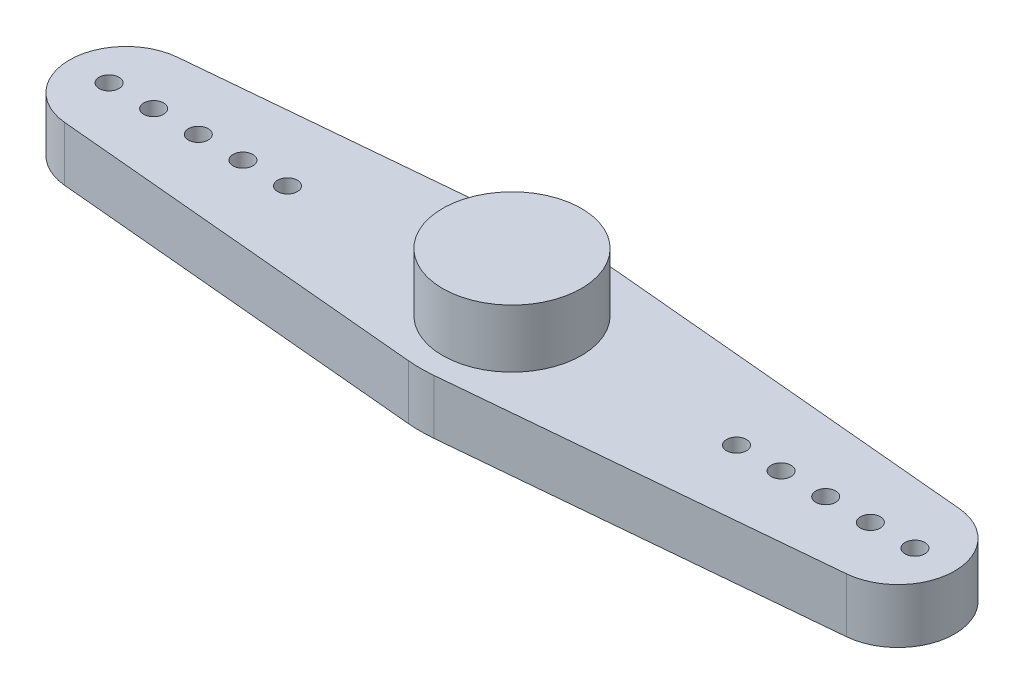
SolidWorks part; units mm, degrees
ref_plane "Front Plane" through (0, 0, 0) normal (0, 0, 1) x (1, 0, 0)
ref_plane "Top Plane" through (0, 0, 0) normal (0, 1, 0) x (1, 0, 0)
ref_plane "Right Plane" through (0, 0, 0) normal (1, 0, 0) x (0, 0, -1)
sketch "Sketch1" plane through (0, 0, 0) normal (0, 1, 0) x (1, 0, 0)
  line L0 (-27.25, 0) -> (27.25, 0) construction
  line L1 (27.613, 3.9835) -> (0, 6.5)
  line L2 (0, -6.5) -> (27.613, -3.9835)
  line L3 (28.45, 0) -> (25.3, 0) construction
  line L4 (0, -6.5) -> (0, 6.5) construction
  line L5 (-28.45, 0) -> (-25.3, 0) construction
  line L6 (0, -6.5) -> (-27.613, -3.9835)
  line L7 (-27.613, 3.9835) -> (0, 6.5)
  circle A0 centre (0, 0) radius 6.5 construction
  arc A1 (27.613, -3.9835) -> (27.613, 3.9835) centre (27.25, 0) ccw
  circle A2 centre (28.45, 0) radius 0.7
  circle A7 centre (25.3, 0) radius 0.7
  circle A8 centre (22.15, 0) radius 0.7
  circle A9 centre (19, 0) radius 0.7
  circle A10 centre (15.85, 0) radius 0.7
  circle A11 centre (-15.85, 0) radius 0.7
  circle A12 centre (-19, 0) radius 0.7
  circle A13 centre (-22.15, 0) radius 0.7
  circle A14 centre (-25.3, 0) radius 0.7
  circle A15 centre (-28.45, 0) radius 0.7
  arc A16 (-27.613, -3.9835) -> (-27.613, 3.9835) centre (-27.25, 0) cw
  point P19 (31.25, 0)
  point P36 (-31.25, 0)
  dimension "D1" = 13
  dimension "D2" = 8
  dimension "D4" = 1.4
  dimension "D3" = 27.25
  dimension "D5" = 2.8
  dimension "D7" = 3.15
  dimension "D8" = 15.4
  dimension "D6" = 5
extrude "Boss-Extrude1" add sketch "Sketch1" along normal blind 3.85
fillet "Fillet1" radius 10 2 edges at (0, 1.925, 6.5) (0, 1.925, -6.5)
sketch "Sketch2" plane through (0, 3.85, 0) normal (0, 1, 0) x (1, 0, 0)
  circle A0 centre (0, 0) radius 4.9
  dimension "D1" = 9.8
extrude "Boss-Extrude2" add sketch "Sketch2" along normal blind 4.1
